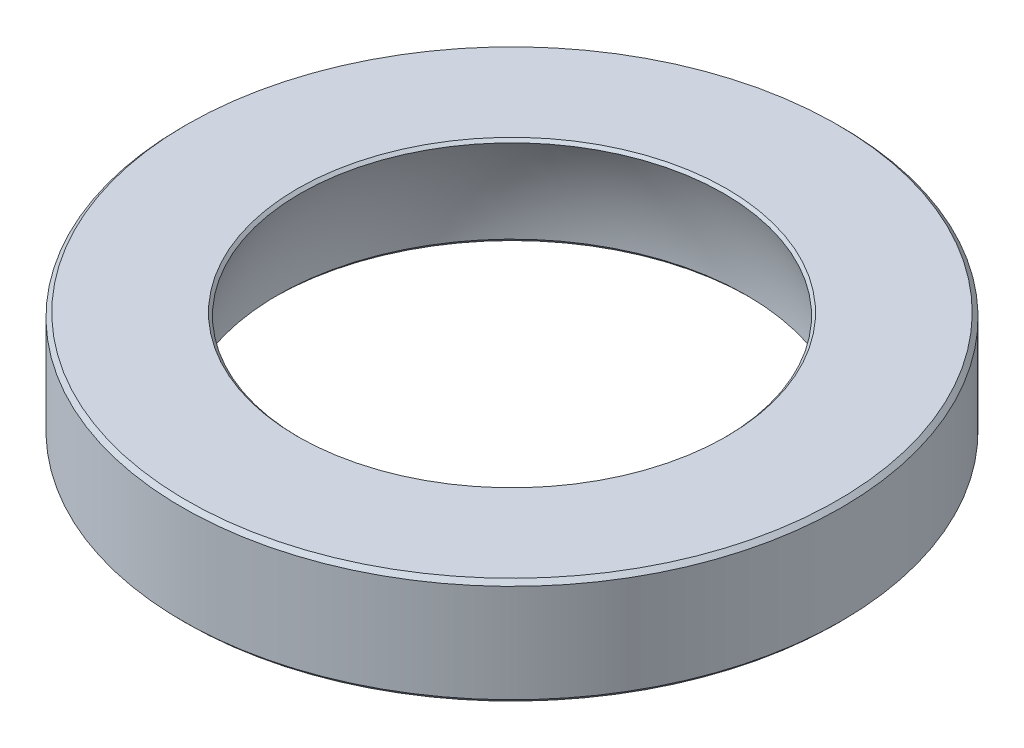
SolidWorks part; units mm, degrees
ref_plane "Front Plane" through (0, 0, 0) normal (0, 0, 1) x (1, 0, 0)
ref_plane "Top Plane" through (0, 0, 0) normal (0, 1, 0) x (1, 0, 0)
ref_plane "Right Plane" through (0, 0, 0) normal (1, 0, 0) x (0, 0, -1)
sketch "Sketch1" plane through (0, 0, 0) normal (0, 0, 1) x (1, 0, 0)
  line L0 (0, 6) -> (0, -6)
  line L1 (0, -6) -> (-6.25, -6)
  line L3 (-6.25, 6) -> (0, 6)
  arc A0 (-6.25, -6) -> (-6.25, 6) centre (0.4582, 0) cw
  point P3 (0, 0)
  dimension "D3" = 9
  dimension "D1" = 6.25
  dimension "D2" = 12
sketch "Sketch2" plane through (0, 0, 0) normal (0, 0, 1) x (1, 0, 0)
  line L0 (-12, -3.875) -> (-7.6649, -3.875)
  line L1 (-12, -3.875) -> (-12, 3.875)
  line L2 (-12, 3.875) -> (-7.6649, 3.875)
  line L3 (0, 6) -> (0, -6) construction
  arc A0 (-6.25, 6) -> (-6.25, -6) centre (0.4582, 0) ccw construction
  arc A1 (-7.6649, 3.875) -> (-7.6649, -3.875) centre (0.4582, 0) ccw
  dimension "D1" = 7.75
  dimension "D2" = 12
revolve "Revolve1" add sketch "Sketch2" angle 360 about L0
sketch "Sketch3" plane through (0, 0, 0) normal (0, 0, 1) x (1, 0, 0)
  line L0 (-12, 3.875) -> (-12, -3.875) construction
  line L1 (-12, 0) -> (22.206, 0)
  line L2 (-12, 0) -> (-12, -8.3925)
  line L3 (-12, -8.3925) -> (22.206, -8.3925)
  line L4 (22.206, 0) -> (22.206, -8.3925)
extrude "Cut-Extrude1" cut sketch "Sketch3" against normal through all both and the other way through all
chamfer "Chamfer1" distance 0.15 angle 45 4 edges at (0, 0, 8.5418) (0, 0, 12) (-7.6649, 3.875, 0) (-12, 3.875, 0)
